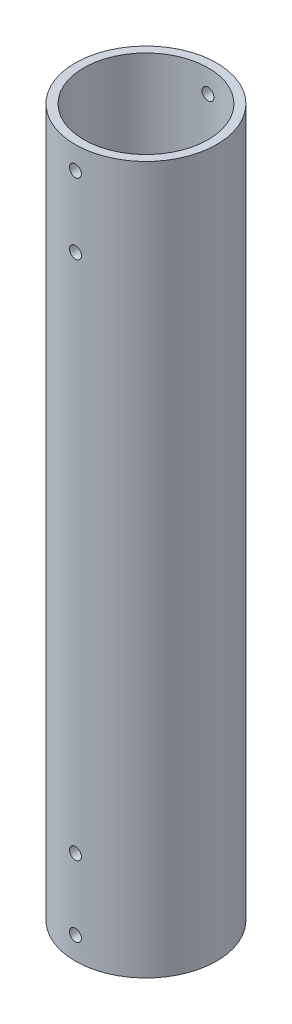
SolidWorks part; units mm, degrees
ref_plane "前视基准面" through (0, 0, 0) normal (0, 0, 1) x (1, 0, 0)
ref_plane "上视基准面" through (0, 0, 0) normal (0, 1, 0) x (1, 0, 0)
ref_plane "右视基准面" through (0, 0, 0) normal (1, 0, 0) x (0, 0, -1)
other "Configuration Table"
sketch "草图1" plane through (0, 0, 0) normal (0, 1, 0) x (1, 0, 0)
  circle A0 centre (0, 0) radius 25
  dimension "D1" = 50
extrude "拉伸-薄壁1" add sketch "草图1" along normal blind 250 thin thin type one direction reverse wall 3
sketch "草图2" plane through (0, 250, 0) normal (0, 1, 0) x (1, 0, 0)
  circle A0 centre (0, 0) radius 20
  dimension "D1" = 40
ref_plane "基准面1" through (0, 265, 0) normal (0, 1, 0) x (1, 0, 0)
ref_plane "基准面2" through (0, 125, 0) normal (0, -1, 0) x (-1, 0, 0)
sketch "草图3" plane through (0, 265, 0) normal (0, 1, 0) x (1, 0, 0)
  circle A0 centre (0, 0) radius 30
  dimension "D1" = 60
sketch "草图4" plane through (0, 0, 0) normal (0, 0, 1) x (1, 0, 0)
  line L0 (30, 265) -> (-30, 265) construction
  line L5 (0, 265) -> (0, 250) construction
  line L6 (20, 250) -> (-20, 250) construction
  arc A0 (-30, 265) -> (-25, 250) centre (-44.9284, 251.6905) cw
  arc A1 (30, 265) -> (25, 250) centre (44.9284, 251.6905) ccw
  dimension "D1" = 20
  dimension "D2" = 30
loft "放样6" [suppressed] add profiles "草图3", "草图2"
shell "抽壳3" [suppressed] thickness 3
sketch "草图5" [suppressed] plane through (0, 215, 0) normal (0, 1, 0) x (1, 0, 0)
  circle A0 centre (0, 0) radius 22.5 construction
  circle A1 centre (0, -22.5) radius 2.1
  circle A2 centre (-19.4856, -11.25) radius 2.1
  circle A3 centre (-19.4856, 11.25) radius 2.1
  circle A4 centre (0, 22.5) radius 2.1
  circle A5 centre (19.4856, 11.25) radius 2.1
  circle A6 centre (19.4856, -11.25) radius 2.1
  dimension "D1" = 45
  dimension "D2" = 4.2
  dimension "D3" = 6
extrude "切除-拉伸1" [suppressed] cut sketch "草图5" against normal blind 20
mirror "镜向3" [suppressed] about plane through (0, 125, 0) normal (0, -1, 0)
shell "抽壳4" [suppressed] thickness 3
mirror "镜向4" [suppressed] about plane through (0, 125, 0) normal (0, -1, 0)
sketch "草图6" plane through (0, 0, 0) normal (0, 0, 1) x (1, 0, 0)
  line L0 (25, 250) -> (-25, 250) construction
  line L1 (-27.5, 125) -> (27.5, 125) construction
  line L2 (25, 0) -> (25, 250) construction
  circle A0 centre (0, 242) radius 2.1
  circle A1 centre (0, 8) radius 2.1
  circle A2 centre (0, 217) radius 2.1
  circle A3 centre (0, 33) radius 2.1
  point P12 (0, 0)
  dimension "D1" = 4.2
  dimension "D2" = 8
  dimension "D3" = 25
  dimension "D4" = 25
extrude "切除-拉伸2" cut sketch "草图6" against normal mid plane 60
